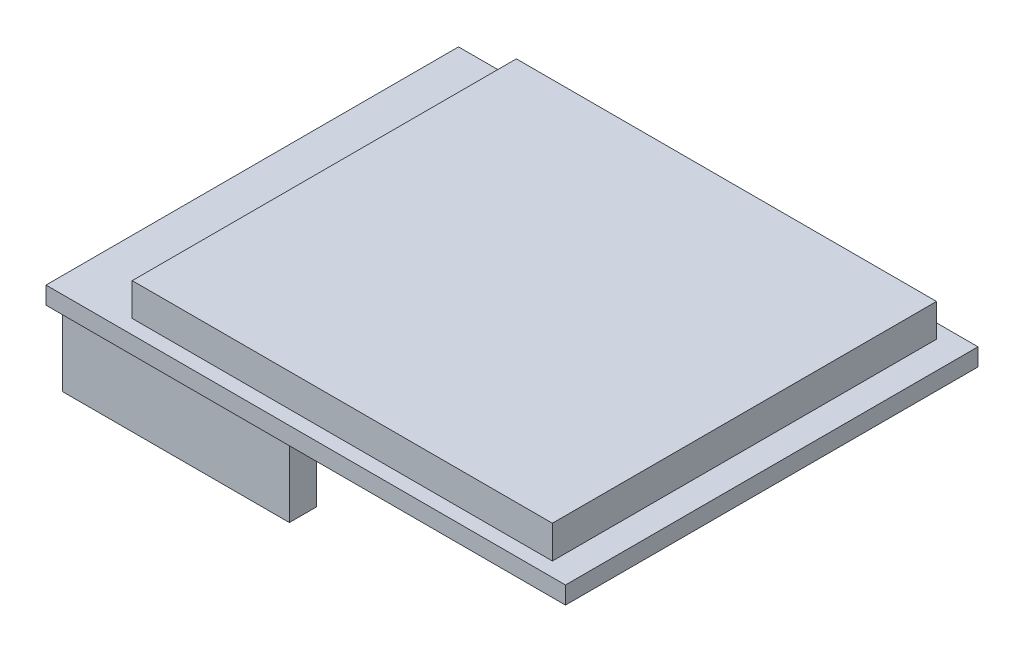
SolidWorks part; units mm, degrees
ref_plane "Front Plane" through (0, 0, 0) normal (0, 0, 1) x (1, 0, 0)
ref_plane "Top Plane" through (0, 0, 0) normal (0, 1, 0) x (1, 0, 0)
ref_plane "Right Plane" through (0, 0, 0) normal (1, 0, 0) x (0, 0, -1)
sketch "Sketch1" plane through (0, 0, 0) normal (0, 1, 0) x (1, 0, 0)
  line L1 (-23.8, -18.9) -> (23.8, -18.9)
  line L2 (-23.8, -18.9) -> (-23.8, 18.9)
  line L3 (-23.8, 18.9) -> (23.8, 18.9)
  line L4 (23.8, -18.9) -> (23.8, 18.9)
  line L5 (-23.8, -18.9) -> (23.8, 18.9) construction
  line L6 (-23.8, 18.9) -> (23.8, -18.9) construction
  point P0 (0, 0)
  dimension "D1" = 47.6
  dimension "D2" = 37.8
extrude "Boss-Extrude1" add sketch "Sketch1" along normal blind 1.6
sketch "Sketch2" plane through (0, 1.6, 0) normal (0, 1, 0) x (1, 0, 0)
  line L0 (0, 0) -> (-11.3276, 0) construction
  line L1 (-17.2, 17.6) -> (21.3, 17.6)
  line L2 (-17.2, 17.6) -> (-17.2, -17.6)
  line L3 (-17.2, -17.6) -> (21.3, -17.6)
  line L4 (21.3, 17.6) -> (21.3, -17.6)
  dimension "D1" = 35.2
  dimension "D2" = 38.5
extrude "Boss-Extrude2" add sketch "Sketch2" along normal blind 3 separate body
sketch "Sketch3" plane through (0, 0, 0) normal (0, -1, 0) x (1, 0, 0)
  line L0 (-23.8, -18.9) -> (-23.8, 18.9) construction
  line L1 (-23.8, 17.4) -> (-3, 17.4)
  line L2 (-23.8, 17.4) -> (-23.8, 14.9)
  line L3 (-23.8, 14.9) -> (-3, 14.9)
  line L4 (-3, 17.4) -> (-3, 14.9)
  line L5 (-23.8, 18.9) -> (23.8, 18.9) construction
  line L6 (0, 0) -> (-7.8377, 0) construction
  line L7 (-3, -17.4) -> (-3, -14.9)
  line L8 (-23.8, -14.9) -> (-3, -14.9)
  line L9 (-23.8, -17.4) -> (-23.8, -14.9)
  line L10 (-23.8, -17.4) -> (-3, -17.4)
  dimension "D1" = 20.8
  dimension "D2" = 2.5
  dimension "D3" = 1.5
extrude "Boss-Extrude3" add sketch "Sketch3" along normal blind 7.6 separate body
